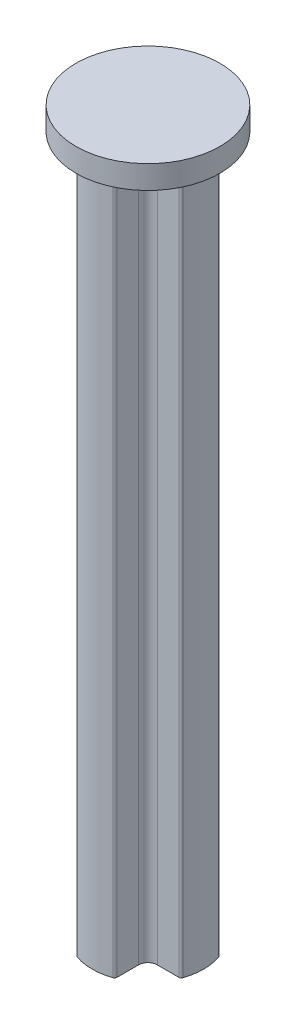
SolidWorks part; units mm, degrees
ref_plane "Front Plane" through (0, 0, 0) normal (0, 0, 1) x (1, 0, 0)
ref_plane "Top Plane" through (0, 0, 0) normal (0, 1, 0) x (1, 0, 0)
ref_plane "Right Plane" through (0, 0, 0) normal (1, 0, 0) x (0, 0, -1)
sketch "Sketch2" plane through (0, 0, 0) normal (0, 1, 0) x (1, 0, 0)
  circle A0 centre (0, 0) radius 3.1
  dimension "D1" = 6.2
extrude "Boss-Extrude1" add sketch "Sketch2" along normal blind 31
sketch "Sketch3" plane through (0, 0, 0) normal (0, 1, 0) x (1, 0, 0)
  line L0 (-0.84, -1.24) -> (-0.84, -2.1777)
  line L2 (-0.84, 2.1777) -> (-0.84, 1.24)
  line L4 (0.84, 2.1777) -> (0.84, 1.24)
  line L5 (-0.84, 2.2482) -> (0.84, -2.2482) construction
  line L6 (-0.84, -2.2482) -> (0.84, 2.2482) construction
  line L7 (-2.1777, 0.84) -> (-1.24, 0.84)
  line L9 (-2.1777, -0.84) -> (-1.24, -0.84)
  line L11 (-2.2482, 0.84) -> (2.2482, -0.84) construction
  line L12 (-2.2482, -0.84) -> (2.2482, 0.84) construction
  line L13 (0.84, -1.24) -> (0.84, -2.1777)
  line L14 (1.24, 0.84) -> (2.1777, 0.84)
  line L15 (1.24, -0.84) -> (2.1777, -0.84)
  arc A0 (-2.2724, 0.7722) -> (-2.2724, -0.7722) centre (0, 0) ccw
  arc A1 (-0.7722, -2.2724) -> (0.7722, -2.2724) centre (0, 0) ccw
  arc A2 (2.2724, -0.7722) -> (2.2724, 0.7722) centre (0, 0) ccw
  arc A3 (0.7722, 2.2724) -> (-0.7722, 2.2724) centre (0, 0) ccw
  arc A4 (-2.1777, 0.84) -> (-2.2724, 0.7722) centre (-2.1777, 0.74) ccw
  arc A5 (-2.2724, -0.7722) -> (-2.1777, -0.84) centre (-2.1777, -0.74) ccw
  arc A6 (-0.84, -2.1777) -> (-0.7722, -2.2724) centre (-0.74, -2.1777) ccw
  arc A7 (0.7722, -2.2724) -> (0.84, -2.1777) centre (0.74, -2.1777) ccw
  arc A8 (2.1777, -0.84) -> (2.2724, -0.7722) centre (2.1777, -0.74) ccw
  arc A9 (2.1777, 0.84) -> (2.2724, 0.7722) centre (2.1777, 0.74) cw
  arc A10 (0.7722, 2.2724) -> (0.84, 2.1777) centre (0.74, 2.1777) cw
  arc A11 (-0.7722, 2.2724) -> (-0.84, 2.1777) centre (-0.74, 2.1777) ccw
  arc A12 (-0.84, -1.24) -> (-1.24, -0.84) centre (-1.24, -1.24) ccw
  arc A13 (0.84, -1.24) -> (1.24, -0.84) centre (1.24, -1.24) cw
  arc A14 (0.84, 1.24) -> (1.24, 0.84) centre (1.24, 1.24) ccw
  arc A15 (-0.84, 1.24) -> (-1.24, 0.84) centre (-1.24, 1.24) cw
  circle A17 centre (0, 0) radius 3.1
  point P42 (0.84, -0.84)
  point P45 (0.84, 0.84)
  dimension "D1" = 4.8
  dimension "D4" = 0.1
  dimension "D5" = 0.4
  dimension "D6" = 6.2
  dimension "D2" = 1.68
  dimension "D3" = 1.68
extrude "Cut-Extrude1" cut sketch "Sketch3" along normal blind 30
